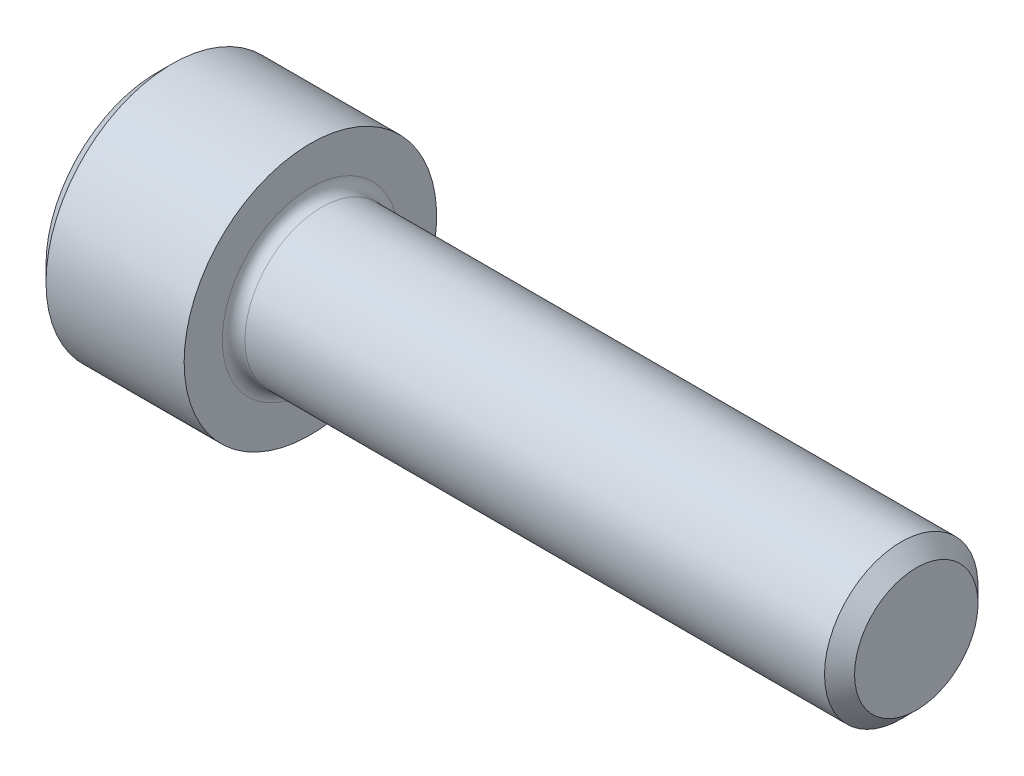
SolidWorks part; units mm, degrees
revolve "Base-Revolve" add sketch "BodySke"
sketch "BodySke" plane through (0, 0, 0) normal (0, 0, 1) x (1, 0, 0)
  line L0 (0, 0) -> (0, 3.4861)
  line L1 (0.4826, 3.9688) -> (4.826, 3.9688)
  line L2 (4.826, 3.9688) -> (4.826, 2.413)
  line L3 (4.826, 2.413) -> (23.4036, 2.413)
  line L4 (23.876, 1.9406) -> (23.876, 0)
  line L5 (23.876, 0) -> (0, 0)
  line L6 (-31.75, 0) -> (127, 0) construction
  line L7 (0, 3.4861) -> (0.4826, 3.9688)
  line L8 (23.876, 1.9406) -> (23.4036, 2.413)
  line L9 (0, -3.4861) -> (0.4826, -3.9688) construction
  line L10 (23.876, -1.9406) -> (23.4036, -2.413) construction
  line L11 (5.6185, 9.525) -> (5.6185, 3.175) construction
  line L12 (4.826, 9.525) -> (4.826, 3.175) construction
  line L13 (-14.224, 9.525) -> (-14.224, 3.175) construction
  dimension "Diameter" = 4.826
  dimension "Head_ht" = 4.826
  dimension "Length" = 19.05
  dimension "Body_ch_ang" = 45
  dimension "Head_dia" = 7.9375
  dimension "Head_ch_ang" = 45
  dimension "Head_side_ht" = 4.3434
  dimension "Minor_dia" = 3.8811
  dimension "Advance" = 0.7925
  dimension "Thread_nom" = 19.05
  dimension "Thread_length" = 38.1
cosmetic thread "ThreadCosmetic" [suppressed]
fillet "Fillet1" radius 0.3556 1 edges at (4.826, 0, 2.413)
ref_plane "Plane1" through (0, 0, 0) normal (0, 0, 1) x (1, 0, 0)
ref_plane "Plane2" through (0, 0, 0) normal (0, 1, 0) x (1, 0, 0)
ref_plane "Plane3" through (0, 0, 0) normal (1, 0, 0) x (0, 0, -1)
sketch "Sketch2" plane through (0, 0, 0) normal (0, 0, 1) x (1, 0, 0)
  line L0 (0, 1.985) -> (2.286, 1.985)
  line L1 (2.286, 1.985) -> (3.432, 0)
  line L2 (-31.75, 0) -> (127, 0) construction
  line L3 (3.432, 0) -> (0, 0)
  line L4 (0, 0) -> (0, 1.985)
  line L5 (0, 3.4861) -> (0, -3.4861) construction
  line L6 (0, 0) -> (47.625, 0) construction
  line L7 (4.826, -3.9688) -> (4.826, 3.9688) construction
  dimension "D1" = 1.985
  dimension "D2" = 60
revolve "Hex-PreBroach" cut sketch "Sketch2" angle 360 about L6
sketch "Sketch3" plane through (0, 0, 0) normal (-1, 0, 0) x (0, 0.5, 0.866)
  line L0 (1.146, 1.985) -> (-1.146, 1.985)
  line L1 (-1.146, 1.985) -> (-2.2921, 0)
  line L2 (1.146, 1.985) -> (2.2921, 0)
  line L3 (1.146, -1.985) -> (2.2921, 0)
  line L4 (1.146, -1.985) -> (-1.146, -1.985)
  line L5 (-1.146, -1.985) -> (-2.2921, 0)
  dimension "D1" = 1.985
  dimension "D2" = 1.985
  dimension "Hex_size" = 3.97
extrude "Hex" cut sketch "Sketch3" against normal blind 2.286
sketch "Sketch4" plane through (0, 0, 0) normal (-1, 0, 0) x (0, 0, 1)
  line L0 (0, 0) -> (2.3876, 0)
  line L1 (0, 0) -> (6.1484, 3.5498) construction
  line L2 (0, 0) -> (1.1938, 2.0677)
  line L3 (1.9883, 0.576) -> (2.2704, 0.7389)
  line L4 (1.493, 1.4339) -> (1.7751, 1.5968)
  arc A0 (1.9883, 0.576) -> (1.493, 1.4339) centre (0, 0) ccw
  arc A1 (2.3876, 0) -> (2.2704, 0.7389) centre (0, 0) ccw
  arc A2 (1.1938, 2.0677) -> (1.7751, 1.5968) centre (0, 0) cw
  dimension "D1" = 30
  dimension "D2" = 60
  dimension "Spline_p_dim" = 0.9906
  dimension "D3" = 0.4953
extrude "Spline" [suppressed] cut sketch "Sketch4" against normal blind 2.286
pattern_circular "CirPattern1" [suppressed] count 6 every 60
sketch "Sketch5" plane through (0, 0, 0) normal (0, 0, 1) x (1, 0, 0)
  line L0 (-31.75, 0) -> (127, 0) construction
  line L2 (0, 3.4861) -> (0, -3.4861) construction
  circle A0 centre (1.651, 0) radius 0.5905
  dimension "Drilled_hole_dia" = 1.1811
  dimension "Drilled_hole_loc" = 1.651
extrude "Hole" [suppressed] cut sketch "Sketch5" against normal through all and the other way through all
pattern_circular "Drilled-4" [suppressed] count 2 every 60
pattern_circular "Drilled-6" [suppressed] count 3 every 60
sketch "ThdSchSke" plane through (0, 0, 0) normal (0, 0, 1) x (1, 0, 0)
  line L0 (5.6185, -1.9406) -> (5.2877, -2.413)
  line L1 (5.6185, -1.9406) -> (5.9493, -2.413)
  line L2 (5.9493, -2.413) -> (5.9493, -3.0163)
  line L3 (-3.175, 0) -> (5.1513, 0) construction
  line L5 (5.9493, -3.0163) -> (5.2877, -3.0163)
  line L6 (5.2877, -3.0163) -> (5.2877, -2.413)
  line L7 (0, 3.4861) -> (0, -3.4861) construction
  dimension "Thread_minor" = 3.8811
  dimension "Diameter" = 4.826
  dimension "Start" = 5.6185
revolve "ThreadSchematic" [suppressed] cut sketch "ThdSchSke" angle 360 about L3
pattern_linear "ThdSchPat" [suppressed]
equation "\"D2@Sketch3\" = \"Hex_size@Sketch3\" / 2"
equation "\"D1@Sketch3\" = \"Hex_size@Sketch3\" / 2"
equation "\"D1@Sketch2\" = \"Hex_size@Sketch3\" / 2"
equation "\"D3@Sketch4\" = \"Spline_p_dim@Sketch4\" / 2"
equation "\"Thread_minor@ThreadCosmetic\"  =  \"Minor_dia@BodySke\""
equation "\"D2@CirPattern1\" = 360 / \"Num_teeth@CirPattern1\""
equation "\"Wall_thickness@Sketch2\" = \"Head_ht@BodySke\" - \"Key_eng@Hex\""
equation "\"Thread_length@ThreadCosmetic\" = ((sgn( (\"Length@BodySke\" - \"Advance@BodySke\" ) - \"Thread_nom@BodySke\" )-1)*( (\"Length@BodySke\" - \"Advance@BodySke\" ) - \"Thread_nom@BodySke\" ))/-2+ \"Thread_nom@BodySke\""
equation "\"Thread_minor@ThdSchSke\" = \"Minor_dia@BodySke\""
equation "\"Diameter@ThdSchSke\" = \"Diameter@BodySke\""
equation "\"Overcut@ThdSchSke\" = \"Diameter@BodySke\" * 1.25"
equation "\"Start@ThdSchSke\" = \"Head_ht@BodySke\" + \"Length@BodySke\" - \"Thread_length@ThreadCosmetic\"  '---Non-countersunk---"
equation "\"Num_threads@ThdSchPat\" = int( \"Thread_length@ThreadCosmetic\" / \"Advance@BodySke\" + 0.999 )  + 1"
equation "\"Advance@ThdSchPat\" = \"Thread_length@ThreadCosmetic\" /  (\"Num_threads@ThdSchPat\" - 1) 'relax it"
equation "\"Num_threads@ThdSchPat\" = \"Num_threads@ThdSchPat\" - sgn( \"Num_threads@ThdSchPat\" - 1) '---chamfered tips only---"
